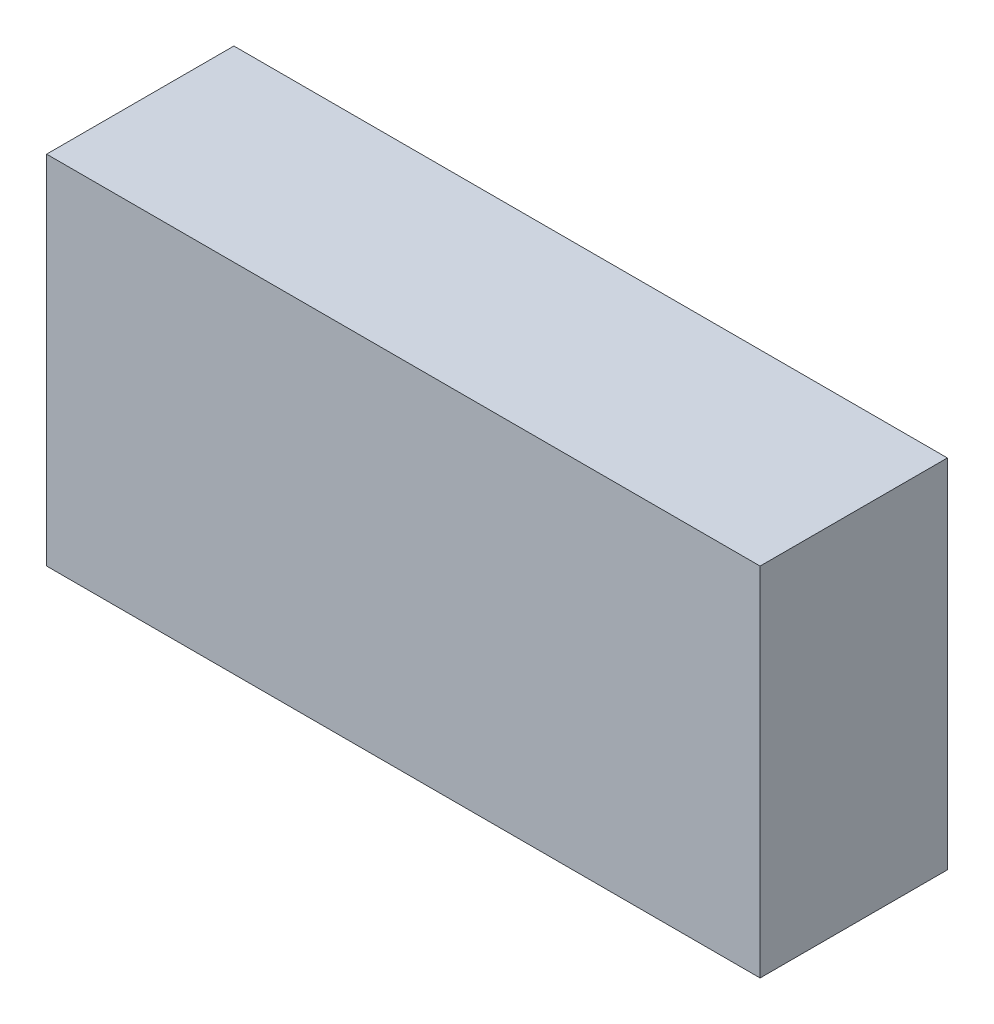
SolidWorks part; units mm, degrees
ref_plane "Front Plane" through (0, 0, 0) normal (0, 0, 1) x (1, 0, 0)
ref_plane "Top Plane" through (0, 0, 0) normal (0, 1, 0) x (1, 0, 0)
ref_plane "Right Plane" through (0, 0, 0) normal (1, 0, 0) x (0, 0, -1)
sketch "Sketch1" plane through (0, 0, 0) normal (0, 0, 1) x (1, 0, 0)
  line L1 (-25.3372, 15.136) -> (-21.3372, 15.136)
  line L2 (-25.3372, 15.136) -> (-25.3372, 13.136)
  line L3 (-25.3372, 13.136) -> (-21.3372, 13.136)
  line L4 (-21.3372, 15.136) -> (-21.3372, 13.136)
  dimension "D1" = 2
  dimension "D2" = 4
extrude "Boss-Extrude1" add sketch "Sketch1" along normal blind 1.05
